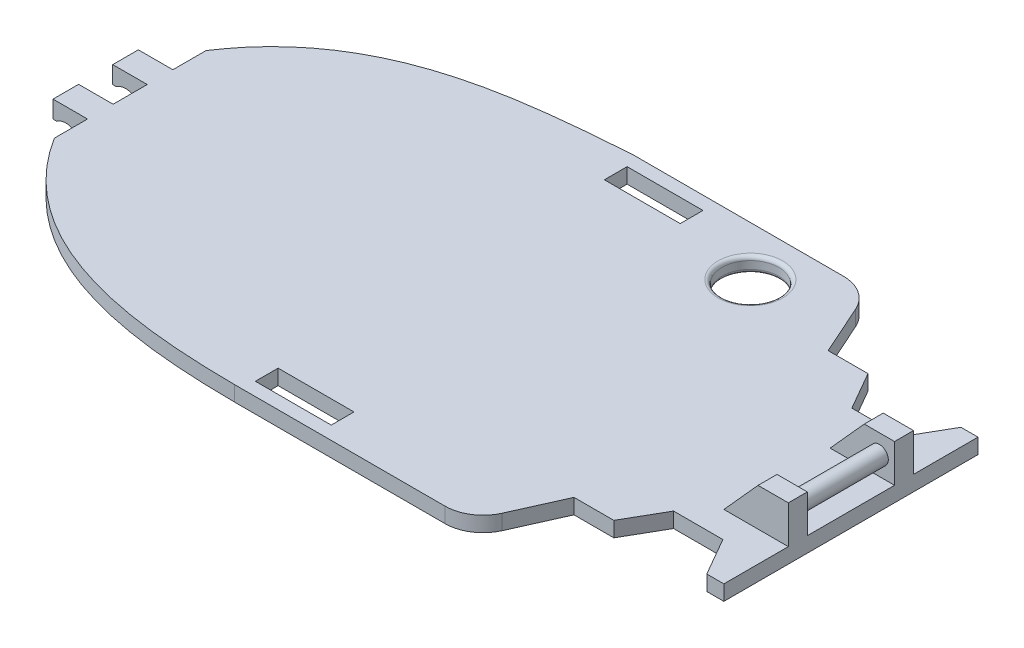
SolidWorks part; units mm, degrees
ref_plane "Front Plane" through (0, 0, 0) normal (0, 0, 1) x (1, 0, 0)
ref_plane "Top Plane" through (0, 0, 0) normal (0, 1, 0) x (1, 0, 0)
ref_plane "Right Plane" through (0, 0, 0) normal (1, 0, 0) x (0, 0, -1)
sketch "Sketch1" plane through (0, 0, 0) normal (0, 1, 0) x (1, 0, 0)
  line L0 (-110, 0) -> (0, 0)
  line L1 (0, 0) -> (0, -105)
  line L2 (0, -105) -> (-110, -105)
  line L4 (-190, -72.5) -> (-190, -32.5)
  spline S0 degree 3 poles (-190, -32.5) (-171.7074, -4.6189) (-138.9899, -2.1787) (-110, 0) knots 0 0 0 0 1 1 1 1
  spline S1 degree 2 poles (-190.0397, -35.2371) (-187.6331, -30.2964) (-183.9056, -25.9107) (-180.479, -21.8792) (-175.9528, -18.3354) (-171.8462, -15.1201) (-166.8566, -12.3231) (-164.564, -11.0379) (-162.0905, -9.8442) (-159.6124, -8.6482) (-157.2765, -7.6915) knots 0 0 0 0.25 0.25 0.5 0.5 0.75 0.75 0.875 0.875 1 1 1 construction
  spline S2 degree 2 poles (-157.2765, -7.6915) (-155.8569, -7.11) (-154.4721, -6.6099) (-153.0466, -6.0951) (-151.6197, -5.6536) (-148.8172, -4.7863) (-145.7427, -4.1123) (-142.8487, -3.4777) (-139.6519, -3.0009) (-136.688, -2.5589) (-133.369, -2.2385) knots 0 0 0 0.125 0.125 0.25 0.25 0.5 0.5 0.75 0.75 1 1 1 construction
  spline S3 degree 3 poles (-190, -72.5) (-172.2628, -100.7004) (-139.266, -104.8361) (-110, -105) knots 0 0 0 0 1 1 1 1
  point P11 (-190, -52.5)
  point P12 (0, -52.5)
  dimension "D4" = 40
  dimension "D1" = 110
  dimension "D2" = 105
  dimension "D3" = 190
  dimension "D5" = 110
extrude "Boss-Extrude1" add sketch "Sketch1" along normal blind 4
sketch "Sketch2" plane through (0, 0, 105) normal (0, 0, 1) x (1, 0, 0)
  line L0 (-190, 4) -> (-201, 4)
  line L1 (-178, 0) -> (-191, -11)
  line L2 (57.75, 0) -> (-57.75, 0) construction
  line L3 (-191, -11) -> (-201, -11)
  line L6 (-190, 4) -> (-178, 0)
  line L7 (-201, 4) -> (-201, -11)
  dimension "D1" = 11
  dimension "D2" = 15
  dimension "D5" = 10
extrude "Boss-Extrude2" add sketch "Sketch2" along normal mid plane 6 from offset 45 offset against normal yes
ref_plane "Plane1" through (0, 0, 52.5) normal (0, 0, 1) x (1, 0, 0)
mirror "Mirror1" about plane through (0, 0, 52.5) normal (0, 0, 1) of "Boss-Extrude2"
ref_plane "Plane2" through (-100, 0, 0) normal (1, 0, 0) x (0, 0, -1)
sketch "Sketch5" plane through (0, 0, 105) normal (0, 0, 1) x (1, 0, 0)
  line L0 (-16.9798, 4) -> (-7.9798, 14)
  line L1 (-110, 4) -> (0, 4) construction
  line L2 (-7.9798, 14) -> (0, 14)
  line L3 (0, 14) -> (0, 4)
  line L4 (0, 4) -> (-16.9798, 4)
  dimension "D1" = 10
  dimension "D2" = 9
extrude "Boss-Extrude3" add sketch "Sketch5" along direction (0, 0, 1) on the side against the normal mid plane 6 from offset 39 contours L2 L3 L4 L0 offset against normal yes
mirror "Mirror4" about plane through (0, 0, 52.5) normal (0, 0, 1) of "Boss-Extrude3"
sketch "Sketch6" plane through (0, 0, 42) normal (0, 0, 1) x (1, 0, 0)
  line L0 (0, -2.2) -> (0, 2.2) construction
  line L1 (-110, 4) -> (0, 4) construction
  circle A0 centre (-4, 10) radius 2.5
  dimension "D1" = 5
  dimension "D2" = 4
  dimension "D3" = 6
extrude "Boss-Extrude4" add sketch "Sketch6" along normal up to body separate body
sketch "Sketch7" plane through (0, 4, 0) normal (0, 1, 0) x (1, 0, 0)
  line L0 (-110, -105) -> (0, -105) construction
  line L1 (-108, -101.5) -> (-88, -101.5)
  line L2 (-108, -101.5) -> (-108, -95.5)
  line L3 (-108, -95.5) -> (-88, -95.5)
  line L4 (-88, -101.5) -> (-88, -95.5)
  dimension "D1" = 2
  dimension "D2" = 20
  dimension "D3" = 6
  dimension "D4" = 3.5
extrude "Cut-Extrude1" cut sketch "Sketch7" against normal blind 10
mirror "Mirror5" about plane through (0, 0, 52.5) normal (0, 0, 1) of "Cut-Extrude1"
sketch "Sketch8" plane through (0, 4, 0) normal (0, 1, 0) x (1, 0, 0)
  line L4 (-88, -3.5) -> (-88, -9.5) construction
  line L5 (-13.75, 0) -> (13.75, 0) construction
  circle A0 centre (-66, -13) radius 7.5
  dimension "D2" = 15
  dimension "D1" = 22
  dimension "D3" = 13
sketch "Sketch9" plane through (0, 0, 52.5) normal (0, 0, 1) x (1, 0, 0)
  line L0 (-66, 4) -> (-163.8674, -3.4662)
  line L1 (-58.5, 4) -> (-73.5, 4) construction
sketch "Sketch10" plane through (0, 4, 0) normal (0, 1, 0) x (1, 0, 0)
  line L0 (0, -19) -> (-39.5, -19)
  line L1 (0, -2.2) -> (0, 2.2) construction
  line L2 (-39.5, -19) -> (-48, 0)
  line L3 (-2.2, 0) -> (2.2, 0) construction
  line L4 (-48, 0) -> (0, 0)
  line L5 (0, 0) -> (0, -19)
  dimension "D1" = 19
  dimension "D2" = 8.5
  dimension "D3" = 48
extrude "Cut-Extrude2" cut sketch "Sketch10" against normal through all both and the other way through all contours L2 L4 L5 L0
mirror "Mirror6" about plane through (0, 0, 52.5) normal (0, 0, 1) of "Cut-Extrude2"
fillet "Fillet1" radius 10 2 edges at (-48, 2, 0) (-48, 2, 105)
sketch "Sketch11" plane through (0, 4, 0) normal (0, 1, 0) x (1, 0, 0)
  line L0 (-4.5, -19) -> (-10.25, -29)
  line L1 (0, -19) -> (-39.5, -19) construction
  line L2 (-10.25, -29) -> (-23.25, -29)
  line L3 (-23.25, -29) -> (-29, -19)
  line L4 (-29, -19) -> (-4.5, -19)
  point P9 (-16.75, -19)
  point P10 (-16.75, -29)
  dimension "D2" = 10.5
  dimension "D3" = 10
  dimension "D4" = 13
extrude "Cut-Extrude3" cut sketch "Sketch11" against normal through all both and the other way through all
mirror "Mirror7" about plane through (0, 0, 52.5) normal (0, 0, 1) of "Cut-Extrude3"
sketch "Sketch12" plane through (0, 0, 0) normal (1, 0, 0) x (0, 0, -1)
  line L0 (-63, 14) -> (-64, 14) construction
  line L1 (-69, 14) -> (-63, 14) construction
  line L2 (-42, 14) -> (-41, 14) construction
  line L3 (-36, 14) -> (-42, 14) construction
  line L4 (-41, 14) -> (-41, 3.5219) construction
  line L5 (-42, 4) -> (-38.9627, 4) construction
  line L7 (-64, 14) -> (-41, 14)
  line L8 (-64, 14) -> (-64, 4)
  line L9 (-64, 4) -> (-41, 4)
  line L10 (-41, 14) -> (-41, 4)
extrude "Cut-Extrude6" cut sketch "Sketch12" against normal blind 21
sketch "Sketch13" plane through (0, 0, 64) normal (0, 0, -1) x (-1, 0, 0)
  line L0 (7.9798, 14) -> (7.9798, 4.2522) construction
  line L1 (0, 14) -> (7.9798, 4) construction
  line L2 (0, 13.75) -> (0, -13.75) construction
  line L3 (7.9798, 14) -> (0, 14) construction
  line L4 (0, 4) -> (4.5, 4) construction
  line L5 (0, 4) -> (7.9798, 14) construction
  circle A0 centre (3.9899, 9) radius 2.35
  dimension "D1" = 4.7
extrude "Boss-Extrude5" add sketch "Sketch13" along normal up to next
sketch "Sketch14" plane through (0, 0, 52.5) normal (0, 0, 1) x (1, 0, 0)
  line L0 (-201, 4) -> (-201, -11) construction
  line L1 (-201, 4) -> (-201, -11) construction
  line L2 (-190, 4) -> (-201, -11) construction
  line L4 (-201, 4) -> (-191, -11) construction
  line L5 (-198.0957, 4) -> (-198.0957, -0.5654)
  line L6 (-190, 4) -> (-201, 4) construction
  line L7 (-201, -11) -> (-191, -11) construction
  line L8 (-198.0957, -11) -> (-202.7192, -12.1152)
  line L9 (-202.7192, -12.1152) -> (-202.5885, 4.843)
  line L10 (-202.5885, 4.843) -> (-198.0957, 4)
  line L11 (-198.0957, -6.9618) -> (-198.0957, -11)
  arc A0 (-198.0957, -6.9618) -> (-198.0957, -0.5654) centre (-195.6933, -3.7636) ccw
extrude "Cut-Extrude7" cut sketch "Sketch14" against normal through all both and the other way through all
sketch "Sketch15" plane through (-198.0957, 0, 0) normal (-1, 0, 0) x (0, 0, 1)
  line L4 (63, 4) -> (57, 4)
  line L5 (57, 4) -> (57, -0.5654)
  line L6 (57, -0.5654) -> (63, -0.5654)
  line L7 (63, -0.5654) -> (63, 4)
  line L8 (63, 4) -> (57, 4)
  line L9 (57, 4) -> (57, -0.5654)
  line L10 (57, -0.5654) -> (63, -0.5654)
  line L11 (63, -0.5654) -> (63, 4)
  line L12 (42, -0.5654) -> (48, -0.5654)
  line L13 (48, -0.5654) -> (48, 4)
  line L14 (48, 4) -> (42, 4)
  line L15 (42, 4) -> (42, -0.5654)
  line L16 (42, -0.5654) -> (48, -0.5654)
  line L17 (48, -0.5654) -> (48, 4)
  line L18 (48, 4) -> (42, 4)
  line L19 (42, 4) -> (42, -0.5654)
  line L20 (42, -11) -> (48, -11)
  line L21 (48, -11) -> (48, -6.9618)
  line L22 (48, -6.9618) -> (42, -6.9618)
  line L23 (42, -6.9618) -> (42, -11)
  line L24 (42, -11) -> (48, -11)
  line L25 (48, -11) -> (48, -6.9618)
  line L26 (48, -6.9618) -> (42, -6.9618)
  line L27 (42, -6.9618) -> (42, -11)
  line L28 (63, -6.9618) -> (57, -6.9618)
  line L29 (57, -6.9618) -> (57, -11)
  line L30 (57, -11) -> (63, -11)
  line L31 (63, -11) -> (63, -6.9618)
  line L32 (63, -6.9618) -> (57, -6.9618)
  line L33 (57, -6.9618) -> (57, -11)
  line L34 (57, -11) -> (63, -11)
  line L35 (63, -11) -> (63, -6.9618)
  dimension "D1" = 0
  dimension "D2" = 0
  dimension "D3" = 0
  dimension "D4" = 0
extrude "Boss-Extrude6" add sketch "Sketch15" along normal blind 1
extrude "Cut-Extrude8" cut sketch "Sketch8" against normal blind 10 contours A0
fillet "Fillet2" radius 1 2 edges at (-66, 0, 20.5) (-66, 4, 20.5)
sketch "Sketch16" plane through (0, 0, 42) normal (0, 0, -1) x (-1, 0, 0)
  line L9 (198.0957, -0.5654) -> (199.0957, -0.5654)
  line L10 (199.0957, -0.5654) -> (199.0957, 4)
  line L11 (199.0957, 4) -> (190, 4)
  line L12 (190, 4) -> (190, 0)
  line L13 (190, 0) -> (178, 0)
  line L14 (178, 0) -> (191, -11)
  line L15 (191, -11) -> (199.0957, -11)
  line L16 (199.0957, -11) -> (199.0957, -6.9618)
  line L17 (199.0957, -6.9618) -> (198.0957, -6.9618)
  line L18 (198.0957, -0.5654) -> (199.0957, -0.5654)
  line L19 (199.0957, -0.5654) -> (199.0957, 4)
  line L20 (199.0957, 4) -> (190, 4)
  line L21 (190, 4) -> (190, 0)
  line L22 (190, 0) -> (178, 0)
  line L23 (178, 0) -> (191, -11)
  line L24 (191, -11) -> (199.0957, -11)
  line L25 (199.0957, -11) -> (199.0957, -6.9618)
  line L26 (199.0957, -6.9618) -> (198.0957, -6.9618)
  arc A1 (198.0957, -0.5654) -> (198.0957, -6.9618) centre (195.6933, -3.7636) ccw
  arc A2 (198.0957, -0.5654) -> (198.0957, -6.9618) centre (195.6933, -3.7636) ccw
  dimension "D1" = 0
extrude "Boss-Extrude7" add sketch "Sketch16" along normal blind 0.75
sketch "Sketch17" plane through (0, 0, 63) normal (0, 0, 1) x (1, 0, 0)
  line L9 (-190, 4) -> (-199.0957, 4)
  line L10 (-199.0957, 4) -> (-199.0957, -0.5654)
  line L11 (-199.0957, -0.5654) -> (-198.0957, -0.5654)
  line L12 (-198.0957, -6.9618) -> (-199.0957, -6.9618)
  line L13 (-199.0957, -6.9618) -> (-199.0957, -11)
  line L14 (-199.0957, -11) -> (-191, -11)
  line L15 (-191, -11) -> (-178, 0)
  line L16 (-178, 0) -> (-190, 0)
  line L17 (-190, 0) -> (-190, 4)
  line L18 (-190, 4) -> (-199.0957, 4)
  line L19 (-199.0957, 4) -> (-199.0957, -0.5654)
  line L20 (-199.0957, -0.5654) -> (-198.0957, -0.5654)
  line L21 (-198.0957, -6.9618) -> (-199.0957, -6.9618)
  line L22 (-199.0957, -6.9618) -> (-199.0957, -11)
  line L23 (-199.0957, -11) -> (-191, -11)
  line L24 (-191, -11) -> (-178, 0)
  line L25 (-178, 0) -> (-190, 0)
  line L26 (-190, 0) -> (-190, 4)
  arc A1 (-198.0957, -6.9618) -> (-198.0957, -0.5654) centre (-195.6933, -3.7636) ccw
  arc A2 (-198.0957, -6.9618) -> (-198.0957, -0.5654) centre (-195.6933, -3.7636) ccw
  dimension "D1" = 0
extrude "Boss-Extrude8" add sketch "Sketch17" along normal blind 0.75
